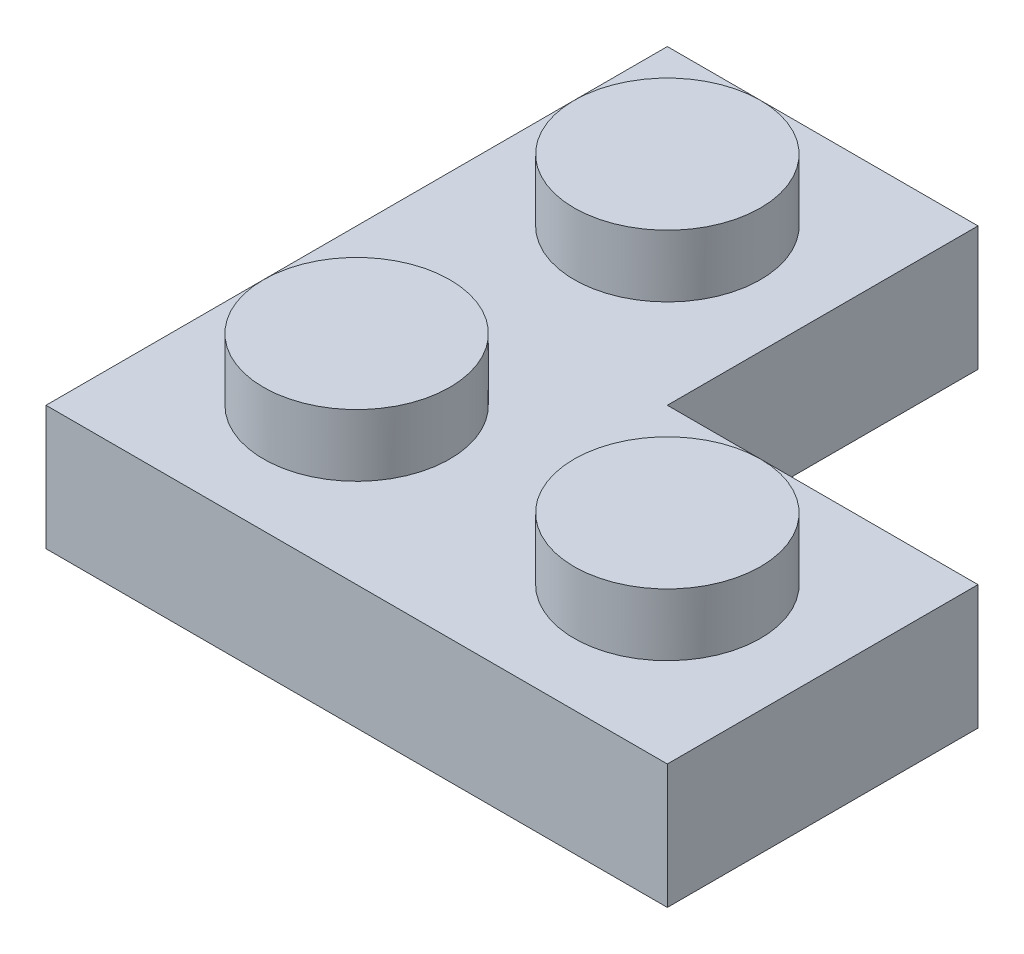
SolidWorks part; units mm, degrees
ref_plane "Front Plane" through (0, 0, 0) normal (0, 0, 1) x (1, 0, 0)
ref_plane "Top Plane" through (0, 0, 0) normal (0, 1, 0) x (1, 0, 0)
ref_plane "Right Plane" through (0, 0, 0) normal (1, 0, 0) x (0, 0, -1)
sketch "Sketch1" plane through (0, 0, 0) normal (0, 1, 0) x (1, 0, 0)
  line L0 (0, 0) -> (0, 16)
  line L1 (0, 16) -> (8, 16)
  line L2 (8, 16) -> (8, 8)
  line L3 (8, 8) -> (16, 8)
  line L4 (16, 8) -> (16, 0)
  line L5 (16, 0) -> (0, 0)
  dimension "D1" = 16
  dimension "D2" = 16
  dimension "D3" = 8
  dimension "D4" = 8
extrude "Boss-Extrude1" add sketch "Sketch1" along normal blind 3.2
sketch "Sketch2" plane through (0, 3.2, 0) normal (0, 1, 0) x (1, 0, 0)
  line L0 (0, 0) -> (4, 0) construction
  line L1 (0, 0) -> (16, 0) construction
  line L2 (4, 0) -> (4, 4) construction
  line L3 (4, 4) -> (4, 12) construction
  line L4 (4, 4) -> (12, 4) construction
  circle A0 centre (4, 4) radius 2.4
  circle A1 centre (4, 12) radius 2.4
  circle A2 centre (12, 4) radius 2.4
  dimension "D5" = 4.8
  dimension "D6" = 4.8
  dimension "D7" = 4.8
  dimension "D1" = 4
  dimension "D2" = 4
  dimension "D3" = 8
  dimension "D4" = 8
extrude "Boss-Extrude2" add sketch "Sketch2" along normal blind 1.6
shell "Shell1" thickness 1.6
